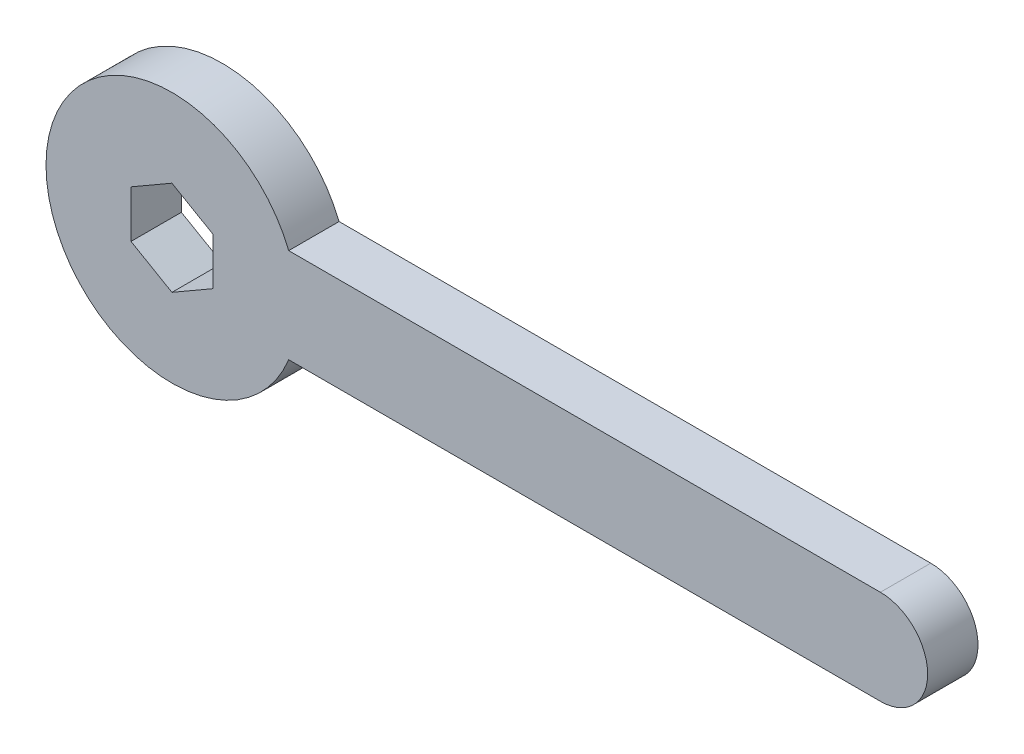
SolidWorks part; units mm, degrees
ref_plane "前视基准面" through (0, 0, 0) normal (0, 0, 1) x (1, 0, 0)
ref_plane "上视基准面" through (0, 0, 0) normal (0, 1, 0) x (1, 0, 0)
ref_plane "右视基准面" through (0, 0, 0) normal (1, 0, 0) x (0, 0, -1)
sketch "草图1" plane through (0, 0, 0) normal (0, 0, 1) x (1, 0, 0)
  circle A0 centre (0, 0) radius 20
extrude "凸台-拉伸1" add sketch "草图1" along normal blind 8
sketch "草图4" plane through (0, 0, 0) normal (0, 0, 1) x (1, 0, 0)
  line L0 (0, -7.5) -> (112.5, -7.5)
  line L1 (112.5, 7.5) -> (0, 7.5)
  arc A0 (112.5, -7.5) -> (112.5, 7.5) centre (112.5, 0) ccw
  arc A1 (0, 7.5) -> (0, -7.5) centre (0, 0) ccw
extrude "凸台-拉伸3" add sketch "草图4" along normal blind 8
sketch "草图5" plane through (0, 0, 0) normal (0, 0, 1) x (1, 0, 0)
  line L0 (6.5, 3.7528) -> (0, 7.5056)
  line L1 (0, 7.5056) -> (-6.5, 3.7528)
  line L2 (-6.5, 3.7528) -> (-6.5, -3.7528)
  line L3 (-6.5, -3.7528) -> (0, -7.5056)
  line L4 (0, -7.5056) -> (6.5, -3.7528)
  line L5 (6.5, -3.7528) -> (6.5, 3.7528)
extrude "切除-拉伸2" cut sketch "草图5" along normal through all
